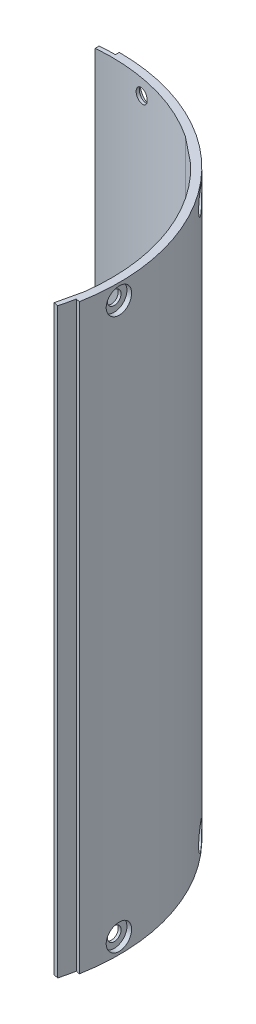
SolidWorks part; units mm, degrees
ref_plane "Спереди" through (0, 0, 0) normal (0, 0, 1) x (1, 0, 0)
ref_plane "Сверху" through (0, 0, 0) normal (0, 1, 0) x (1, 0, 0)
ref_plane "Справа" through (0, 0, 0) normal (1, 0, 0) x (0, 0, -1)
sketch "Эскиз2" plane through (0, 0, 0) normal (0, 1, 0) x (1, 0, 0)
  line L0 (0, -1000) -> (0, 49000) construction
  line L1 (47.1356, -12.7936) -> (48.2666, -13.0514)
  line L2 (33.9524, 35.3303) -> (27.0476, 40.8587) construction
  line L3 (48.5627, -6.5315) -> (46.5973, -15.1557) construction
  line L5 (33.9524, 35.3303) -> (27.0476, 40.8587)
  line L6 (48.5627, -6.5315) -> (46.5973, -15.1557) construction
  line L7 (-3.9968, 48.8367) -> (-3.9968, 49.84)
  line L10 (0, 50) -> (0, 49) construction
  line L12 (0, 0) -> (47.58, -10.8436) construction
  line L16 (47.58, -10.8436) -> (49.725, -11.3324) construction
  line L17 (47.1356, -12.7936) -> (48.5627, -6.5315)
  line L18 (49.1554, -9.1514) -> (50.1312, -9.3737)
  line L19 (0, 50) -> (0, 51)
  circle A0 centre (0, 0) radius 51 construction
  arc A1 (50.1312, -9.3737) -> (0, 51) centre (0, 0) ccw
  circle A2 centre (0, 0) radius 51 construction
  arc A3 (48.5627, -6.5315) -> (33.9524, 35.3303) centre (0, 0) ccw construction
  arc A4 (0, 51) -> (0, -51) centre (0, 0) ccw construction
  arc A5 (48.5627, -6.5315) -> (33.9524, 35.3303) centre (0, 0) ccw
  arc A6 (-3.9968, 48.8367) -> (27.0476, 40.8587) centre (0, 0) cw
  arc A7 (0, -51) -> (49.725, -11.3324) centre (0, 0) ccw construction
  arc A8 (49.725, -11.3324) -> (50.1312, -9.3737) centre (0, 0) ccw construction
  arc A9 (27.0476, 40.8587) -> (-27.0476, 40.8587) centre (0, 0) ccw construction
  arc A10 (0, 50) -> (-3.9968, 49.84) centre (0, 0) ccw
  arc A11 (49.1554, -9.1514) -> (48.2666, -13.0514) centre (0, 0) cw
  point P6 (0, 0)
  point P25 (48.6525, -11.088)
  dimension "D1" = 3.9968
  dimension "D2" = 4
extrude "Бобышка-Вытянуть2" add sketch "Эскиз2" along normal up to surface (149 mm away)
ref_plane "Плоскость5" through (51, 0, 0) normal (1, 0, 0) x (0, 0, -1)
sketch "Эскиз15" plane through (51, 0, 0) normal (1, 0, 0) x (0, 0, -1)
  line L0 (0, -1000) -> (0, 49000) construction
  circle A0 centre (0, 4) radius 3.25
  dimension "D1" = 6.5
  dimension "D2" = 4
extrude "Вырез-Вытянуть5" cut sketch "Эскиз15" against normal blind 1.3
sketch "Эскиз16" plane through (49.7, 0, 0) normal (1, 0, 0) x (0, 0, -1)
  circle A0 centre (0, 4) radius 3.25 construction
  circle A1 centre (0, 4) radius 3.25 construction
  circle A2 centre (0, 4) radius 1.75
  dimension "D1" = 3.5
extrude "Вырез-Вытянуть6" cut sketch "Эскиз16" against normal through all
pattern_circular "Круговой массив3" count 5 every 20 about axis through (0, 0, 0) along (0, 1, 0) skipping 1, 3 of "Вырез-Вытянуть5", "Вырез-Вытянуть6"
sketch "Эскиз17" plane through (51, 0, 0) normal (1, 0, 0) x (0, 0, -1)
  line L0 (0, -1000) -> (0, 49000) construction
  line L1 (51, 149) -> (-9.3737, 149) construction
  circle A0 centre (0, 145) radius 3.25
  circle A1 centre (0, 4) radius 3.25 construction
  dimension "D1" = 4
extrude "Вырез-Вытянуть7" cut sketch "Эскиз17" against normal blind 1.3
sketch "Эскиз18" plane through (49.7, 0, 0) normal (1, 0, 0) x (0, 0, -1)
  circle A0 centre (0, 145) radius 3.25 construction
  circle A1 centre (0, 145) radius 3.25 construction
  circle A2 centre (0, 145) radius 1.75
  circle A3 centre (0, 4) radius 1.75 construction
extrude "Вырез-Вытянуть8" cut sketch "Эскиз18" against normal through all
pattern_circular "Круговой массив5" count 5 every 20 about axis through (0, 149, 0) along (0, 1, 0) skipping 1, 3 of "Вырез-Вытянуть8", "Вырез-Вытянуть7"
